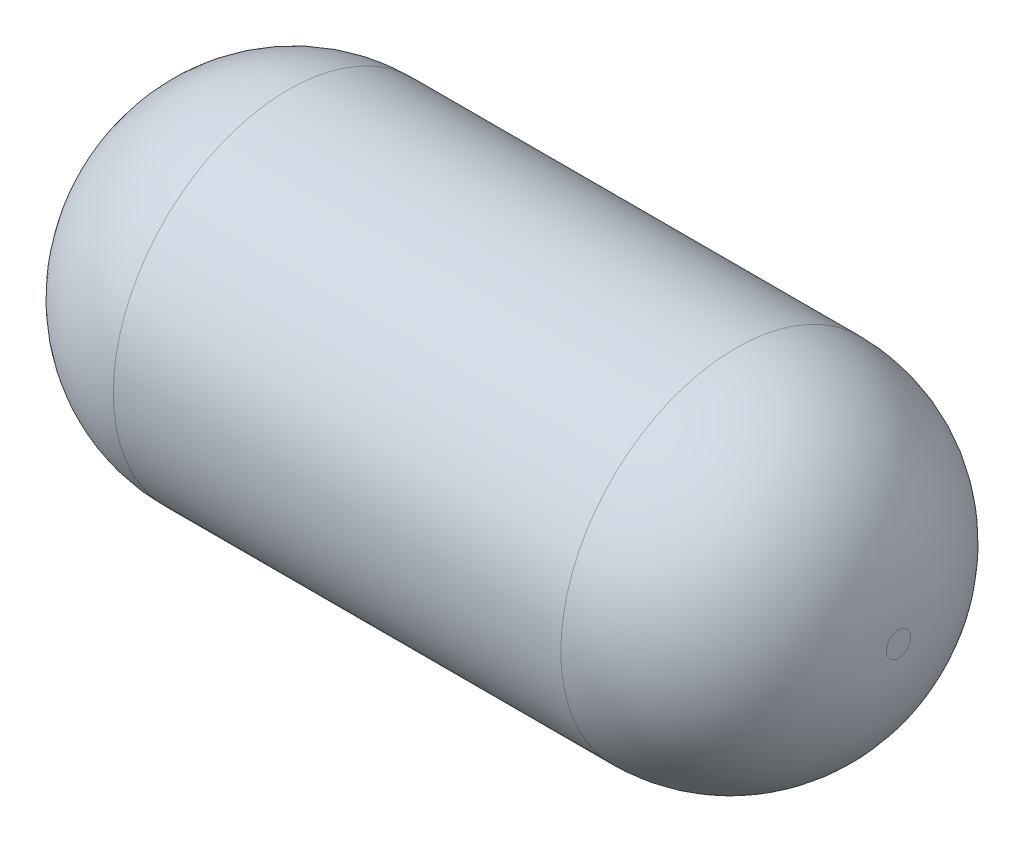
SolidWorks part; units mm, degrees
ref_plane "Front Plane" through (0, 0, 0) normal (0, 0, 1) x (1, 0, 0)
ref_plane "Top Plane" through (0, 0, 0) normal (0, 1, 0) x (1, 0, 0)
ref_plane "Right Plane" through (0, 0, 0) normal (1, 0, 0) x (0, 0, -1)
sketch "Sketch1" plane through (0, 0, 0) normal (0, 1, 0) x (1, 0, 0)
  line L2 (-75.6144, 0) -> (165.6856, 0)
  line L3 (-75.6144, 0) -> (-75.6144, 3.81)
  line L4 (-24.8144, 54.61) -> (114.8856, 54.61)
  line L5 (165.6856, 0) -> (165.6856, 3.81)
  arc A0 (-24.8144, 54.61) -> (-75.6144, 3.81) centre (-24.8144, 3.81) ccw
  arc A1 (165.6856, 3.81) -> (114.8856, 54.61) centre (114.8856, 3.81) ccw
  dimension "D1" = 50.8
  dimension "D2" = 50.8
revolve "Revolve1" add sketch "Sketch1" angle 360 about L2
